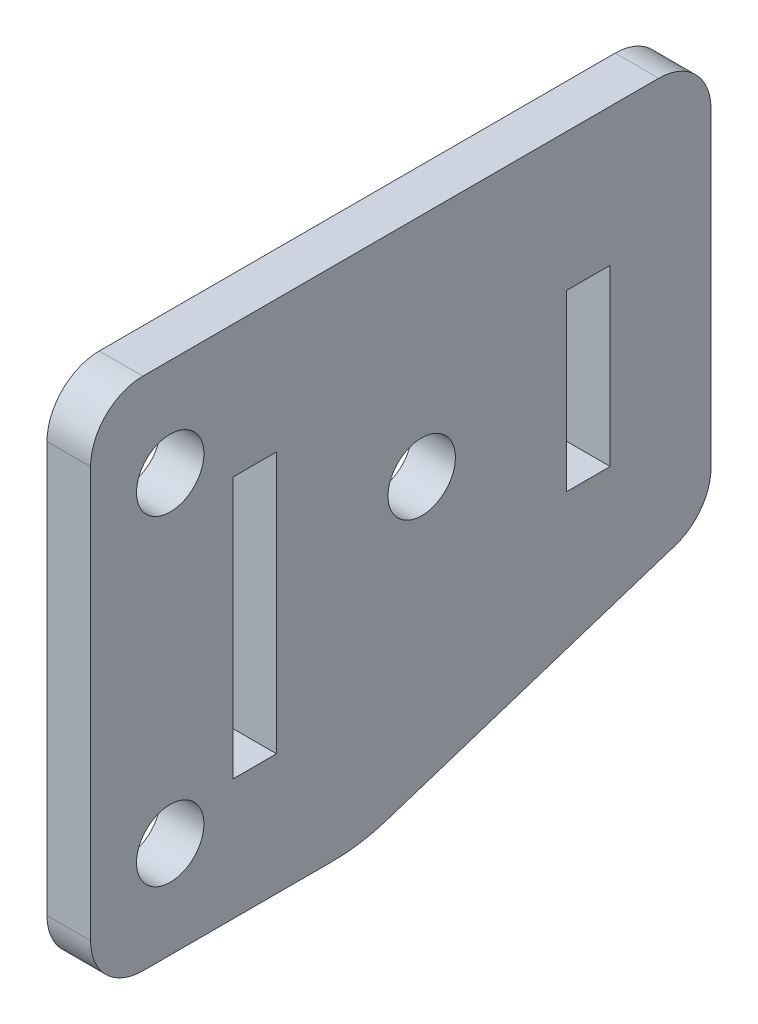
SolidWorks part; units mm, degrees
material "Custom Plastic"
ref_plane "X-Y Datum" through (0, 0, 0) normal (0, 0, 1) x (1, 0, 0)
ref_plane "X-Z Datum" through (0, 0, 0) normal (0, 1, 0) x (1, 0, 0)
ref_plane "Y-Z Datum" through (0, 0, 0) normal (1, 0, 0) x (0, 0, -1)
sketch "Sketch1" plane through (0, 0, 0) normal (1, 0, 0) x (0, 0, -1)
  line L2 (-11.43, 25.4) -> (-56.642, 25.4)
  line L3 (-56.642, 25.4) -> (-56.642, -12.131)
  line L4 (0, 0) -> (-50000, 0) construction
  line L5 (0, 0) -> (0, 50000) construction
  line L6 (-38.9981, -12.131) -> (-39.2035, -12.131) construction
  line L7 (-35.0766, -11.5105) -> (-1.9116, -0.7438) construction
  line L8 (-38.9981, -12.131) -> (-39.2035, -12.131)
  line L9 (-35.0766, -11.5105) -> (-11.43, -3.8338)
  line L10 (-39.2035, -12.131) -> (-63.5, -12.131) construction
  line L11 (-39.2035, -12.131) -> (-56.642, -12.131)
  line L13 (-11.43, -3.8338) -> (-11.43, 25.4)
  line L14 (0, -0.2833) -> (0, 25.4) construction
  line L15 (0, 25.4) -> (-118.0696, 25.4) construction
  arc A0 (-38.9981, -12.131) -> (-35.0766, -11.5105) centre (-38.9981, 0.569) ccw construction
  arc A1 (-38.9981, -12.131) -> (-35.0766, -11.5105) centre (-38.9981, 0.569) ccw
  point P1 (0, 0)
  point P12 (0, 0)
  point P16 (-11.43, -3.8338)
  point P18 (0, 0)
  point P19 (-11.43, 23.6439)
  point P25 (0, 0)
  point P26 (0, 0)
  point P27 (-11.7282, -3.8338)
  dimension "D2" = 56.642
  dimension "D3" = 11.43
extrude "Boss-Extrude1" add sketch "Sketch1" against normal blind 3.175
hole_wizard "#10 (0.1935) Diameter Hole1" positions "Sketch2" profile "Sketch3" hole size "#10" standard "ANSI Inch"
sketch "Sketch2" plane through (0, 0, 0) normal (1, 0, 0) x (0, 0, -1)
  line L2 (-11.43, 25.4) -> (-56.642, 25.4) construction
  line L4 (-46.2661, 25.4) -> (-46.2661, 15.748) construction
  line L5 (-46.2661, -3.302) -> (-46.2661, -12.1412) construction
  point P0 (-50.8381, -5.08)
  point P2 (-50.8381, 18.288)
  point P4 (-32.512, 8.89)
  point P7 (-44.1073, -3.4211)
  point P8 (-44.1073, 18.2261)
  point P9 (-26.1329, 9.833)
  point P12 (0, 0)
  dimension "D1" = 4.572
  dimension "D2" = 30.48
  dimension "D3" = 4.572
  dimension "D4" = 7.112
  dimension "D6" = 16.51
sketch "Sketch3" plane through (0, -5.08, 50.8381) normal (0, 1, 0) x (0, 0, -1)
  line L0 (0, 0) -> (0, 12.6526)
  line L1 (0, 12.6526) -> (2.4574, 11.176)
  line L2 (2.4574, 11.176) -> (2.4574, 0)
  line L5 (2.4574, 0) -> (0, 0)
  line L10 (0, 12.6526) -> (-2.4575, 11.176) construction
  line L11 (0, -6.35) -> (0, 107.95) construction
  dimension "Hole Dia." = 4.9149
  dimension "Hole Depth" = 11.176
  dimension "Drill Angle" = 118
sketch "Sketch6" plane through (-3.175, 0, 0) normal (-1, 0, 0) x (0, 0, 1)
  line L0 (46.2661, 15.748) -> (46.2661, -3.302)
  line L1 (46.2661, -3.302) -> (43.0911, -3.302)
  line L2 (43.0911, -3.302) -> (43.0911, 15.748)
  line L3 (43.0911, 15.748) -> (46.2661, 15.748)
  line L4 (21.9521, 15.371) -> (18.7771, 15.371)
  line L5 (18.7771, 15.371) -> (18.7771, 2.671)
  line L6 (18.7771, 2.671) -> (21.9521, 2.671)
  line L7 (21.9521, 2.671) -> (21.9521, 15.371)
  point P6 (21.9431, 2.8079)
  point P8 (0, 0)
  point P9 (21.9439, 2.8128)
  point P10 (21.9442, 2.812)
  point P11 (18.7733, 2.8021)
  point P12 (0, 0)
  point P13 (0, 0)
  point P14 (0, 0)
  point P15 (0, 0)
  point P16 (0, 0)
  point P17 (0, 0)
  point P18 (0, 0)
  point P19 (0, 0)
  point P28 (0, 0)
  point P29 (0, 0)
extrude "Cut-Extrude1" cut sketch "Sketch6" against normal through all
fillet "Fillet1" radius 3.81 4 edges at (-1.5875, 25.4, 56.642) (-1.5875, -12.131, 56.642) (-1.5875, 25.4, 11.43) (-1.5875, -3.8338, 11.43)
